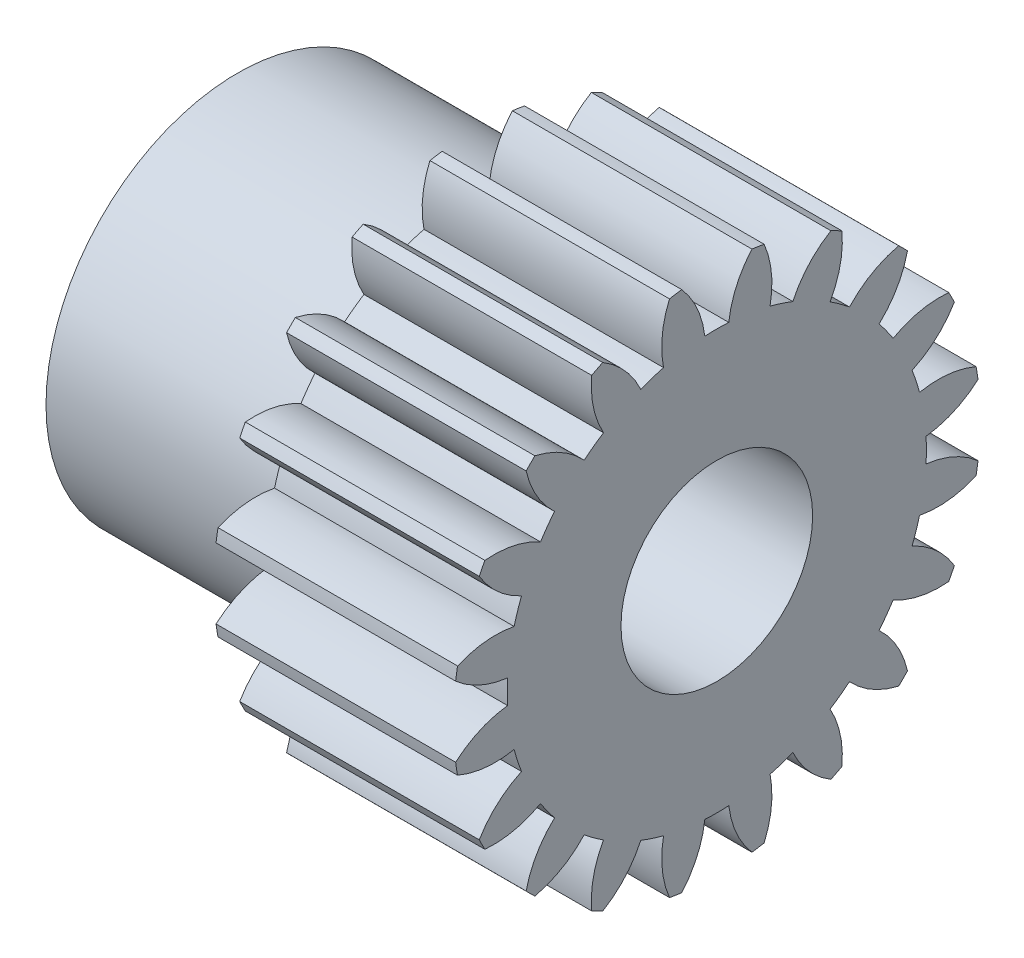
SolidWorks part; units mm, degrees
ref_plane "Plane1" through (0, 0, 0) normal (0, 0, 1) x (1, 0, 0)
ref_plane "Plane2" through (0, 0, 0) normal (0, 1, 0) x (1, 0, 0)
ref_plane "Plane3" through (0, 0, 0) normal (1, 0, 0) x (0, 0, -1)
sketch "HoldingSke" plane through (0, 0, 0) normal (0, 1, 0) x (1, 0, 0)
  line L0 (0, 0) -> (1.8794, -0.684)
  line L1 (-15, 0) -> (100, 0) construction
  line L2 (0, 0) -> (-2.1039, 2.3779)
  line L3 (0, 0) -> (-11.863, 4.5341)
  line L4 (0, 0) -> (8.1152, 2.9537)
  line L5 (0, 0) -> (-4.6848, -1.7473)
  line L6 (0, 0) -> (-4.1448, -2.7965)
  line L7 (-2.1039, 2.3779) -> (-1.0276, 7.2607)
  line L8 (-76.2, 54.61) -> (-75.5, 54.61)
  line L9 (-71.009, 38.7566) -> (-53.1078, 45.2721)
  line L10 (-76.2, 71.12) -> (104.1128, 71.12)
  line L11 (0, 0) -> (-5, 0)
  line L12 (-76.2, 101.6) -> (-76.181, 101.6)
  line L13 (24.9733, 27.94) -> (52.9518, 28.4284)
  line L14 (24.9733, 27.94) -> (24.9743, 27.94)
  line L15 (24.9733, 27.94) -> (100.4006, 29.5858)
  line L16 (-63.627, -0.5) -> (-12.827, -0.5)
  circle A0 centre (0, 0) radius 2
  circle A1 centre (0, 0) radius 4
  circle A2 centre (0, 0) radius 4
  circle A3 centre (0, 0) radius 2
  dimension "MHD" = 8
  dimension "Hub_dia" = 8
  dimension "Bore" = 4
  dimension "MBD" = 4
  dimension "Num_teeth" = 20
  dimension "Pitch" = 2
  dimension "Overall_len" = 5
  dimension "Show_teeth" = 20
  dimension "Thickness" = 5
  dimension "OAL" = 5.0001
  dimension "T_dim" = 0.7
  dimension "Ap" = 20
  dimension "H" = 19.05
  dimension "Pitch_radius" = 180.3128
  dimension "Width" = 5
  dimension "Backlash" = 0.019
  dimension "Addendum_fac" = 1
  dimension "Dedendum_fac" = 1.25
  dimension "Clearance_fac" = 0.25
  dimension "Dedendum_add" = 0.001
  dimension "Module" = 0.5
sketch "BasProSke" plane through (0, 0, 0) normal (0, 1, 0) x (1, 0, 0)
  line L0 (-10, 0) -> (60, 0) construction
  line L1 (0, 0) -> (0, 5.5)
  line L2 (0, 0) -> (5, 0)
  line L3 (5, 0) -> (5, 5.5)
  line L4 (5, 5.5) -> (0, 5.5)
  dimension "Thickness" = 5
  dimension "Diameter" = 11
revolve "Base-Revolve" add sketch "BasProSke" angle 360 about L0
sketch "TooCutSke" plane through (0, 0, 0) normal (1, 0, 0) x (0, 0, -1)
  line L1 (0, 0) -> (0, 107) construction
  line L2 (0, 0) -> (-0.4255, 4.9819) construction
  line L3 (0, 0) -> (-1.5603, 9.8514) construction
  line L4 (-0.4255, 4.9819) -> (-0.7802, 4.9257) construction
  arc A0 (0.2499, 4.3669) -> (-0.2499, 4.3669) centre (0, 0) ccw
  arc A1 (0.7528, 5.4739) -> (-0.7528, 5.4739) centre (0, 0) ccw
  circle A2 centre (0, 0) radius 5 construction
  circle A3 centre (0, 0) radius 4.6985 construction
  arc A4 (-0.2499, 4.3669) -> (-0.7528, 5.4739) centre (-2.2361, 4.1322) ccw
  arc A5 (0.7528, 5.4739) -> (0.2499, 4.3669) centre (2.2361, 4.1322) ccw
  dimension "Root_dia" = 8.748
  dimension "Overcut_dia" = 11.0508
  dimension "Pitch_dia" = 10
  dimension "Base_dia" = 9.3969
  dimension "Flank_rad" = 2
  dimension "Half_ang" = 9
  dimension "Half_CT" = 0.359
extrude "ToothCut" cut sketch "TooCutSke" along normal through all
fillet "Breaks" [suppressed] radius 0.01
fillet "RootFillets" [suppressed] radius 0.126
pattern_circular "TeethCuts" count 20 every 18 about axis through (-10, 0, 0) along (1, 0, 0) of "ToothCut", "RootFillets", "Breaks"
sketch "HubNeaOneSke" plane through (0, 0, 0) normal (-1, 0, 0) x (0, 0, 1)
  circle A0 centre (0, 0) radius 4
  dimension "Diameter" = 8
extrude "HubNearOne" add sketch "HubNeaOneSke" along normal blind 5
sketch "HubNeaBotSke" plane through (0, 0, 0) normal (-1, 0, 0) x (0, 0, 1)
  circle A0 centre (0, 0) radius 4
  dimension "Diameter" = 8
extrude "HubNearBoth" [suppressed] add sketch "HubNeaBotSke" along normal blind 22.5
ref_plane "FarPln" through (5, 0, 0) normal (1, 0, 0) x (0, 0, -1)
sketch "HubFarSke" plane through (5, 0, 0) normal (1, 0, 0) x (0, 0, -1)
  circle A0 centre (0, 0) radius 4
  dimension "Diameter" = 8
extrude "HubFar" [suppressed] add sketch "HubFarSke" along normal blind 22.5
sketch "BorSke" plane through (0, 0, 0) normal (1, 0, 0) x (0, 0, -1)
  circle A0 centre (0, 0) radius 2
  dimension "Diameter" = 4
extrude "Bore" cut sketch "BorSke" along normal mid plane 10.0001
sketch "KeySke" plane through (0, 0, 0) normal (1, 0, 0) x (0, 0, -1)
  line L0 (-0.8, 0) -> (-0.8, 2.7)
  line L1 (-0.8, 2.7) -> (0.8, 2.7)
  line L2 (0.8, 2.7) -> (0.8, 0)
  line L3 (0, 0) -> (0, 34) construction
  line L4 (-0.8, 0) -> (0.8, 0)
  dimension "Offset" = 2.7
  dimension "Width" = 1.6
extrude "Keyway" [suppressed] cut sketch "KeySke" along normal mid plane 10.0001
pattern_circular "Keyway2" [suppressed] count 2 every 90 about axis through (-10, 0, 0) along (1, 0, 0)
equation "' \"Module@HoldingSke\" = 6.35"
equation "' \"Num_teeth@HoldingSke\" = 12"
equation "' \"Ap@HoldingSke\" =  20"
equation "' \"Ap@HoldingSke\" = 20"
equation "' \"Width@HoldingSke\" = 0.5 * 25.4"
equation "' \"Hub_dia@HoldingSke\"= 1 * 25.4"
equation "' \"Hub_dia@HoldingSke\" = 1 * 25.4"
equation "' \"Overall_len@HoldingSke\" = 1.0 * 25.4"
equation "' \"Bore@HoldingSke\" = 0.75 * 25.4"
equation "' \"T_dim@HoldingSke\" = 0.1 * 25.4"
equation "' \"Width@KeySke\" = 0.25 * 25.4"
equation "' \"Show_teeth@HoldingSke\" = 13"
equation "' \"Backlash@HoldingSke\" = 0.009 * 25.4"
equation "' \"Addendum_fac@HoldingSke\" = 1.0"
equation "' \"Dedendum_fac@HoldingSke\" = 1.25"
equation "' \"Dedendum_add@HoldingSke\" = 0.00005 * 25.4"
equation "' \"Clearance_fac@HoldingSke\" = 0.25"
equation "\"Pitch@HoldingSke\" = 1 / \"Module@HoldingSke\""
equation "\"Overcut_dia@TooCutSke\" = (\"Num_teeth@HoldingSke\" + 2 * \"Addendum_fac@HoldingSke\") / \"Pitch@HoldingSke\" + 0.002 * 25.4"
equation "\"Pitch_dia@TooCutSke\" = \"Num_teeth@HoldingSke\" / \"Pitch@HoldingSke\""
equation "\"Base_dia@TooCutSke\" = \"Num_teeth@HoldingSke\" / \"Pitch@HoldingSke\" * cos((\"Ap@HoldingSke\"  * 3.14159265 / 180))"
equation "\"Root_dia@TooCutSke\" = (\"Num_teeth@HoldingSke\" + 2) / \"Pitch@HoldingSke\" - 2 * (\"Addendum_fac@HoldingSke\" + \"Dedendum_fac@HoldingSke\") / \"Pitch@HoldingSke\" - \"Dedendum_add@HoldingSke\" * 2"
equation "\"Half_ang@TooCutSke\" = 180 / \"Num_teeth@HoldingSke\""
equation "\"Half_CT@TooCutSke\" = \"Num_teeth@HoldingSke\" / \"Pitch@HoldingSke\" * sin((3.14159265 / 2 / \"Num_teeth@HoldingSke\")) / 2 - 7 * \"Backlash@HoldingSke\" / 4"
equation "\"Flank_rad@TooCutSke\" = \"Num_teeth@HoldingSke\" / \"Pitch@HoldingSke\" / 5"
equation "\"Radius@RootFillets\" = \"Clearance_fac@HoldingSke\" / \"Pitch@HoldingSke\" + \"Dedendum_add@HoldingSke\""
equation "\"Break_rad@Breaks\" = 0.02 / \"Pitch@HoldingSke\""
equation "\"Thickness@HoldingSke\" = \"Width@HoldingSke\""
equation "\"OAL@HoldingSke\" = \"Thickness@HoldingSke\""
equation "\"MHD@HoldingSke\" = (\"Num_teeth@HoldingSke\" + 2) / \"Pitch@HoldingSke\" - 2 * (\"Addendum_fac@HoldingSke\" + \"Dedendum_fac@HoldingSke\")  / \"Pitch@HoldingSke\" - \"Dedendum_add@HoldingSke\" * 2"
equation "\"MBD@HoldingSke\" = (\"Num_teeth@HoldingSke\" + 2) / \"Pitch@HoldingSke\" - 2 * (\"Addendum_fac@HoldingSke\" + \"Dedendum_fac@HoldingSke\")  / \"Pitch@HoldingSke\" - \"Dedendum_add@HoldingSke\" * 2 - 0.002 * 25.4"
equation "\"MHD@HoldingSke\" = ((sgn( \"MHD@HoldingSke\" - \"Hub_dia@HoldingSke\" )-1)*( \"MHD@HoldingSke\" - \"Hub_dia@HoldingSke\" ))/-2+ \"Hub_dia@HoldingSke\""
equation "\"MBD@HoldingSke\" = ((sgn( \"MBD@HoldingSke\" - \"Bore@HoldingSke\" )-1)*( \"MBD@HoldingSke\" - \"Bore@HoldingSke\" ))/-2+ \"Bore@HoldingSke\""
equation "\"OAL@HoldingSke\" = ((sgn( \"OAL@HoldingSke\" - \"Overall_len@HoldingSke\" )+1)*( \"OAL@HoldingSke\" - \"Overall_len@HoldingSke\" ))/2 + \"Overall_len@HoldingSke\" + 0.000002 * 25.4"
equation "\"Num_teeth@TeethCuts\" = int( \"Show_teeth@HoldingSke\" ) + 1"
equation "\"Num_teeth@TeethCuts\" = ((sgn( \"Num_teeth@TeethCuts\" - \"Num_teeth@HoldingSke\" )-1)*( \"Num_teeth@TeethCuts\" - \"Num_teeth@HoldingSke\" ))/-2+ \"Num_teeth@HoldingSke\""
equation "\"Num_teeth@TeethCuts\" = ((sgn( \"Num_teeth@TeethCuts\" - 2.0)+1)*( \"Num_teeth@TeethCuts\" - 2.0))/2 +2.0"
equation "\"Angle@TeethCuts\" = 360.0 / \"Num_teeth@HoldingSke\""
equation "\"Diameter@BasProSke\" = (\"Num_teeth@HoldingSke\" + 2 * \"Addendum_fac@HoldingSke\") / \"Pitch@HoldingSke\""
equation "\"Thickness@BasProSke\"  = \"Thickness@HoldingSke\""
equation "' \"Fillet_rad@BasProSke\" =  \"Thickness@HoldingSke\" * 0.05"
equation "' \"Fillet_rad@BasProSke\" = \"Thickness@HoldingSke\" * 0.05"
equation "\"MHD@HoldingSke\" = ((sgn( \"MHD@HoldingSke\" - \"Root_dia@TooCutSke\" )-1)*( \"MHD@HoldingSke\" - \"Root_dia@TooCutSke\" ))/-2+ \"Root_dia@TooCutSke\""
equation "\"Diameter@HubNeaOneSke\" = \"MHD@HoldingSke\""
equation "\"Diameter@HubNeaBotSke\" = \"MHD@HoldingSke\""
equation "\"Length@HubNearBoth\" = ( \"OAL@HoldingSke\" - \"Thickness@BasProSke\" ) / 2.0"
equation "\"Thickness@FarPln\" = \"Thickness@BasProSke\""
equation "\"Diameter@HubFarSke\" = \"MHD@HoldingSke\""
equation "\"Length@HubFar\" = ( \"OAL@HoldingSke\" - \"Thickness@BasProSke\" ) / 2.0"
equation "\"Diameter@BorSke\" = \"MBD@HoldingSke\""
equation "\"D1@Bore\" = \"OAL@HoldingSke\" * 2.0"
equation "\"D1@Keyway\" = \"OAL@HoldingSke\" * 2.0"
equation "\"Offset@KeySke\" = \"T_dim@HoldingSke\" + \"MBD@HoldingSke\" / 2.0"
